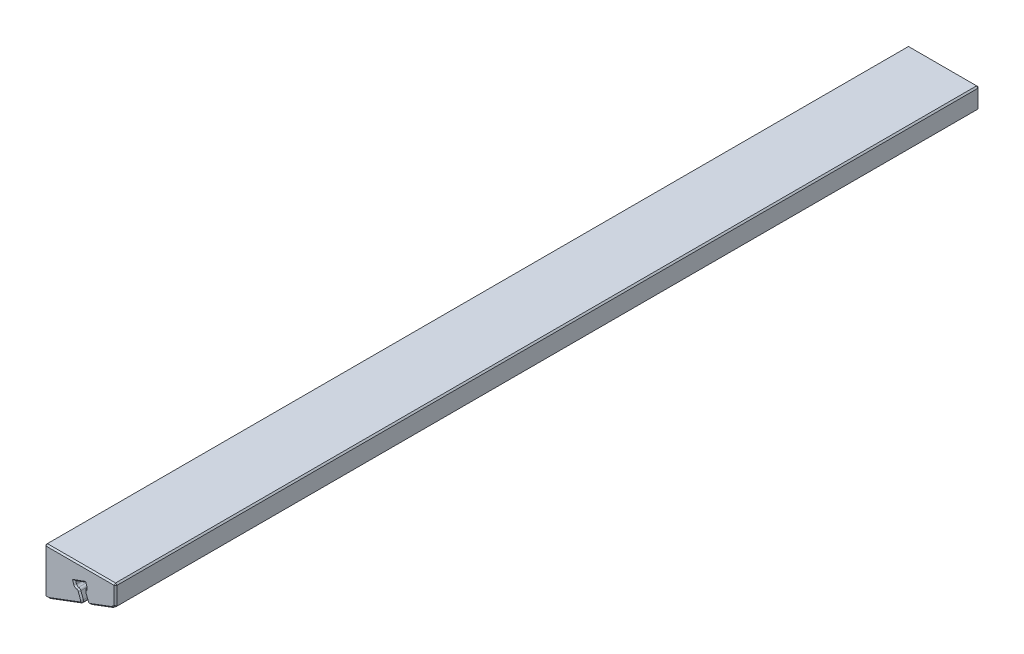
SolidWorks part; units mm, degrees
ref_plane "Front" through (0, 0, 0) normal (0, 0, 1) x (1, 0, 0)
ref_plane "Top" through (0, 0, 0) normal (0, 1, 0) x (1, 0, 0)
ref_plane "Right" through (0, 0, 0) normal (1, 0, 0) x (0, 0, -1)
other "Configuration Table"
sketch "Sketch1" plane through (0, 0, 0) normal (0, 0, 1) x (1, 0, 0)
  line L0 (20, 20) -> (20, 3.5)
  line L1 (0, 0) -> (20, 0) construction
  line L2 (0, 0) -> (0, 20) construction
  line L3 (0, 20) -> (20, 20) construction
  line L4 (20, 0) -> (20, 20) construction
  line L5 (20, 3.5) -> (21.6, 3.5)
  line L6 (21.6, 3.5) -> (25, 7.5277)
  line L7 (25, 7.5277) -> (25, 11.5277)
  line L8 (25, 11.5277) -> (40.0351, 17)
  line L9 (40.0351, 17) -> (44.2306, 12)
  line L10 (44.2306, 12) -> (45.4563, 13.0285)
  line L11 (45.4563, 13.0285) -> (45.4563, 20)
  line L12 (45.4563, 20) -> (20, 20)
  line L13 (10, 20) -> (10, 0) construction
  line L14 (0, 10) -> (20, 10) construction
  point P17 (10, 10)
  point P18 (25, 6.123)
  dimension "D1" = 20
  dimension "D2" = 20
  dimension "D3" = 16
  dimension "D4" = 4
  dimension "D5" = 3.5
  dimension "D6" = 40
  dimension "D7" = 1.6
  dimension "D8" = 2
  dimension "D9" = 70
  dimension "D10" = 5
  dimension "D11" = 1.6
  dimension "D12" = 3
  dimension "D13" = 90
extrude "Boss-Extrude1" add sketch "Sketch1" along normal blind 300
sketch "Sketch2" plane through (25, 0, 0) normal (1, 0, 0) x (0, 0, -1)
  line L0 (-300, 7.5277) -> (0, 7.5277) construction
  line L1 (-300, 13.0285) -> (-300, 20) construction
  point P4 (-275, 7.5277)
  point P5 (-150, 7.5277)
  point P6 (-25, 7.5277)
  dimension "D1" = 25
  dimension "D2" = 125
  dimension "D3" = 125
hole_wizard "CBORE for M3 SBHCS1" positions "Sketch3" profile "Sketch4" counterbore size "M3" standard "ANSI Metric" end condition through all
sketch "Sketch3" plane through (25, 0, 0) normal (1, 0, 0) x (0, 0, -1)
  point P0 (-275, 7.5277)
  point P3 (-150, 7.5277)
  point P6 (-25, 7.5277)
sketch "Sketch4" plane through (25, 7.5277, 275) normal (0, 1, 0) x (0, 0, -1)
  line L0 (0, 0) -> (0, 5)
  line L1 (0, 5) -> (1.8, 5)
  line L3 (1.8, 5) -> (1.8, 1.65)
  line L4 (3.35, 1.65) -> (1.8, 1.65)
  line L5 (3.35, 1.65) -> (3.35, 0.025)
  line L6 (3.35, 0.025) -> (3.375, 0)
  line L7 (3.375, 0) -> (0, 0)
  line L8 (-3.35, 0.025) -> (-3.375, 0) construction
  line L11 (0, -6.35) -> (0, 107.95) construction
  dimension "Thru Hole Dia." = 3.6
  dimension "Thru Hole Depth" = 5
  dimension "C'Bore Dia." = 6.7
  dimension "C'Bore Depth" = 1.65
  dimension "Near C'Sink Dia." = 6.75
  dimension "Near C'Sink Angle" = 90
sketch "Sketch5" plane through (0, 0, 300) normal (0, 0, 1) x (1, 0, 0)
  line L0 (21.6, 3.5) -> (44.2306, 12)
  line L1 (45.4563, 20) -> (20, 20)
  line L2 (45.4563, 20) -> (45.4563, 13.0285)
  line L3 (21.6, 3.5) -> (20, 3.5)
  line L4 (20, 20) -> (20, 3.5)
  line L5 (44.2306, 12) -> (45.4563, 13.0285)
  line L6 (30.6382, 13.5798) -> (34.3969, 14.9479)
  line L7 (25, 11.5277) -> (40.0351, 17) construction
  line L8 (34.3969, 14.9479) -> (34.7213, 14.0841)
  line L9 (34.5578, 13.0976) -> (34.5111, 13.0408)
  line L10 (34.3475, 12.0543) -> (35.5872, 8.7536)
  line L11 (32.5175, 14.2638) -> (34.6511, 8.402) construction
  line L12 (30.6382, 13.5798) -> (30.9448, 12.7096)
  line L13 (32.536, 11.3949) -> (33.7079, 8.0696)
  line L14 (40.0351, 17) -> (44.2306, 12) construction
  line L15 (21.6, 3.5) -> (25, 7.5277) construction
  line L16 (25, 7.5277) -> (25, 11.5277) construction
  line L17 (40.0351, 17) -> (44.2306, 12)
  line L18 (21.6, 3.5) -> (25, 7.5277)
  line L19 (25, 7.5277) -> (25, 11.5277)
  line L20 (25, 11.5277) -> (40.0351, 17)
  line L21 (33.7079, 8.0696) -> (33.7147, 8.0503)
  line L22 (31.7766, 12.0455) -> (31.7043, 12.059)
  arc A0 (34.5578, 13.0976) -> (34.7213, 14.0841) centre (33.7852, 13.7325) ccw
  arc A1 (34.3475, 12.0543) -> (34.5111, 13.0408) centre (35.2837, 12.4059) cw
  arc A2 (31.7043, 12.059) -> (30.9448, 12.7096) centre (31.888, 13.042) cw
  arc A3 (32.536, 11.3949) -> (31.7766, 12.0455) centre (31.5929, 11.0625) ccw
  point P21 (34.9243, 13.5437)
  line M12 (45.4563, 20) -> (20, 20)
  line M13 (20, 20) -> (20, 3.5)
  line M14 (20, 3.5) -> (21.6, 3.5)
  line M15 (21.6, 3.5) -> (25, 7.5277)
  line M16 (25, 7.5277) -> (25, 11.5277)
  line M17 (25, 11.5277) -> (40.0351, 17)
  line M18 (40.0351, 17) -> (44.2306, 12)
  line M19 (44.2306, 12) -> (45.4563, 13.0285)
  line M20 (45.4563, 13.0285) -> (45.4563, 20)
  dimension "D5" = 1
  dimension "D1" = 2
  dimension "D2" = 1.5
  dimension "D3" = 120
  dimension "D4" = 1
extrude "Boss-Extrude2" add sketch "Sketch5" along normal blind 5 contours L13 A3 L22 A2 L12 L0 L21 M17 M16 M15 | A1 L10 L0 L8 A0 L9 M18 M17 | L20 M20 M12 M13 M14 M15 M16 M17 M18 M19
fillet "Fillet1" radius 1 2 edges at (33.7147, 8.0503, 302.5) (35.5872, 8.7536, 302.5)
pattern_linear "LPattern1" count 2 spacing 305 along (0, 0, -1) of "Boss-Extrude2"
chamfer "Chamfer2" distance 0.5 angle 45 67 edges at (33.3523, 8.2193, 300) (40.377, 10.5526, 305) (35.7584, 9.1308, 305) (33.3523, 8.2193, 305) (40.377, 10.5526, 300) (35.7584, 9.1308, 300) (34.5591, 14.516, 0) (34.5344, 13.0692, 0) (34.9674, 10.4039, 0) (39.9089, 10.3768, 0) (27.6574, 5.7751, 0) (32.2434, 11.822, 0) (31.7404, 12.0523, 0) (31.2374, 12.2826, 0) (30.7915, 13.1447, 0) (32.5175, 14.2638, -5) (34.5591, 14.516, -5) (34.7717, 13.569, 0) (34.5344, 13.0692, -5) (34.2971, 12.5694, 0) (34.9674, 10.4039, -5) (39.9089, 10.3768, -5) (44.8434, 12.5142, -5) (45.4563, 16.5142, -5) (32.7281, 20, -5) (20, 11.75, -5) (20.8, 3.5, -5) (27.6574, 5.7751, -5) (33.1254, 9.7226, 0) (32.2434, 11.822, -5) (31.7404, 12.0523, -5) (31.2374, 12.2826, -5) (30.7915, 13.1447, -5) (33.1254, 9.7226, -5) (34.2971, 12.5694, -5) (34.7717, 13.569, -5) (45.4563, 20, 150) (20, 3.5, 150) (20, 20, 150) (30.7915, 13.1447, 300) (32.9625, 10.1846, 300) (34.2971, 12.5694, 300) (34.7717, 13.569, 300) (30.7915, 13.1447, 305) (34.5591, 14.516, 300) (34.7717, 13.569, 305) (34.5344, 13.0692, 300) (34.2971, 12.5694, 305) (34.7916, 10.872, 300) (27.1988, 5.6029, 300) (32.9625, 10.1846, 305) (32.2434, 11.822, 300) (31.7404, 12.0523, 300) (31.2374, 12.2826, 300) (32.5175, 14.2638, 305) (34.5591, 14.516, 305) (34.5344, 13.0692, 305) (34.7916, 10.872, 305) (44.8434, 12.5142, 305) (45.4563, 16.5142, 305) (32.7281, 20, 305) (20, 11.75, 305) (20.8, 3.5, 305) (27.1988, 5.6029, 305) (32.2434, 11.822, 305) (31.7404, 12.0523, 305) (31.2374, 12.2826, 305)
fillet "Fillet2" radius 1 2 edges at (35.5872, 8.7536, -2.5) (33.7147, 8.0503, -2.5)
